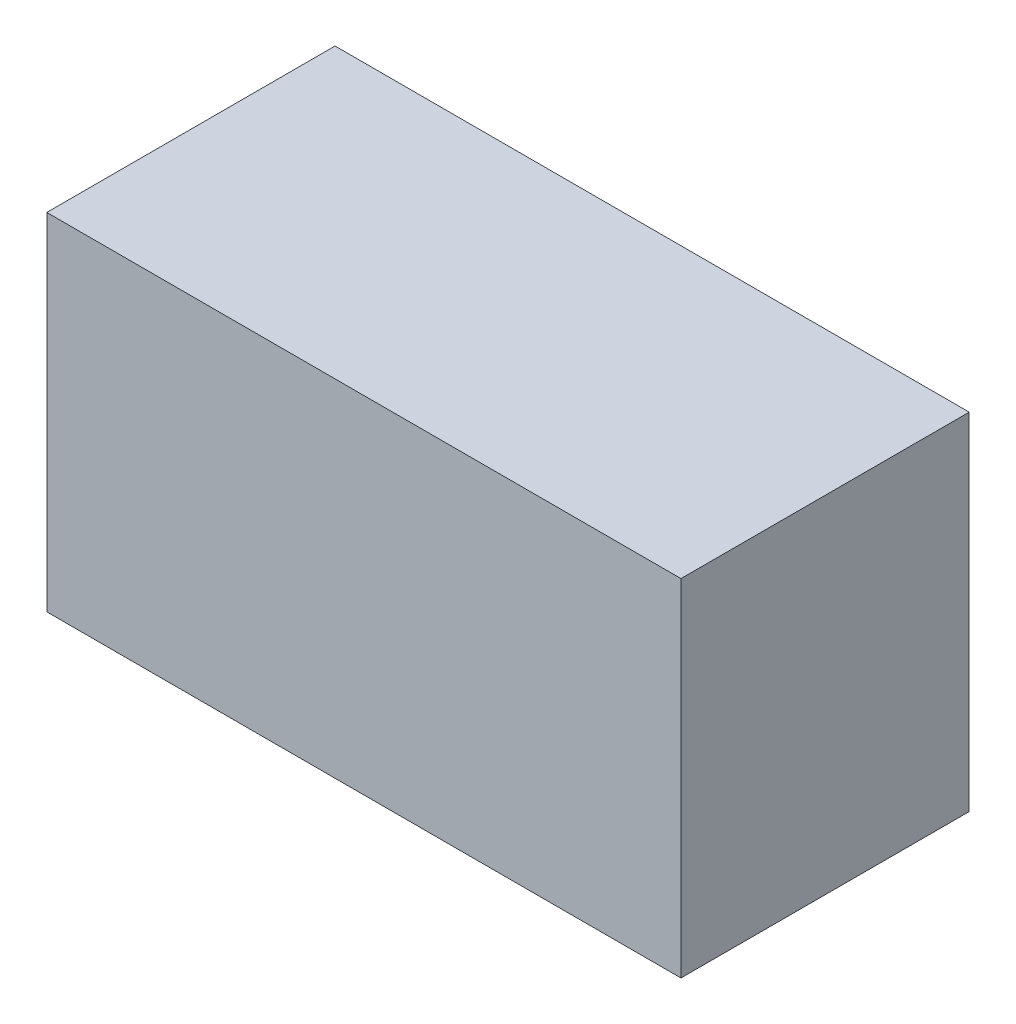
SolidWorks part; units mm, degrees
ref_plane "Front" through (0, 0, 0) normal (0, 0, 1) x (1, 0, 0)
ref_plane "Top" through (0, 0, 0) normal (0, 1, 0) x (1, 0, 0)
ref_plane "Right" through (0, 0, 0) normal (1, 0, 0) x (0, 0, -1)
sketch "Эскиз1" plane through (0, 0, 0) normal (0, 0, 1) x (1, 0, 0)
  line L1 (-5.5, -3) -> (5.5, -3)
  line L2 (-5.5, -3) -> (-5.5, 3)
  line L3 (-5.5, 3) -> (5.5, 3)
  line L4 (5.5, -3) -> (5.5, 3)
  line L5 (-5.5, -3) -> (5.5, 3) construction
  line L6 (-5.5, 3) -> (5.5, -3) construction
  point P0 (0, 0)
extrude "Бобышка-Вытянуть1" add sketch "Эскиз1" along normal blind 5
